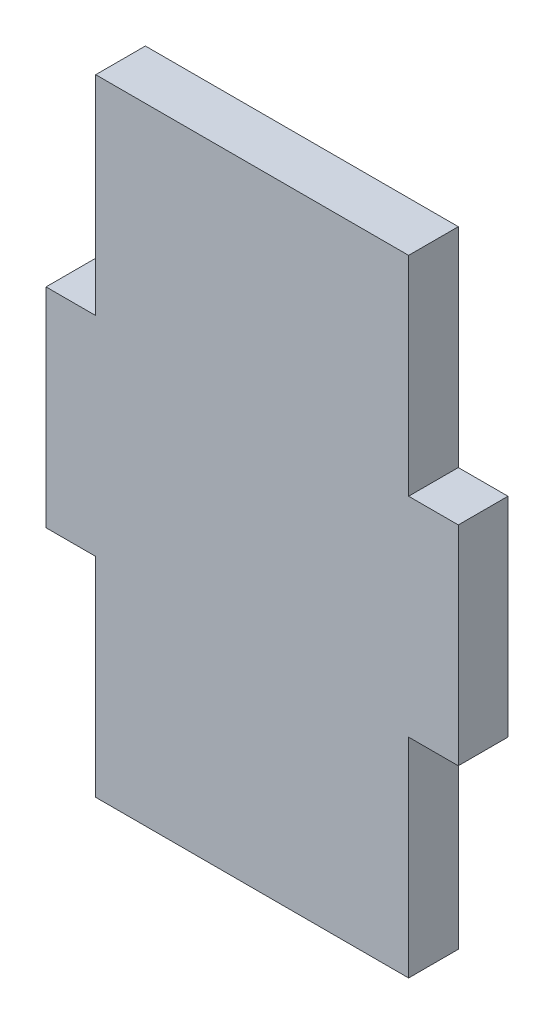
SolidWorks part; units mm, degrees
ref_plane "Front Plane" through (0, 0, 0) normal (0, 0, 1) x (1, 0, 0)
ref_plane "Top Plane" through (0, 0, 0) normal (0, 1, 0) x (1, 0, 0)
ref_plane "Right Plane" through (0, 0, 0) normal (1, 0, 0) x (0, 0, -1)
sketch "Sketch1" plane through (0, 0, 0) normal (0, 0, 1) x (1, 0, 0)
  line L0 (0, 26.6667) -> (-3.175, 26.6667)
  line L1 (0, 0) -> (20, 0)
  line L2 (0, 0) -> (0, 13.3333)
  line L3 (0, 40) -> (20, 40)
  line L4 (20, 0) -> (20, 13.3333)
  line L5 (-3.175, 26.6667) -> (-3.175, 13.3333)
  line L6 (-3.175, 13.3333) -> (0, 13.3333)
  line L7 (20, 26.6667) -> (23.175, 26.6667)
  line L8 (23.175, 26.6667) -> (23.175, 13.3333)
  line L9 (23.175, 13.3333) -> (20, 13.3333)
  line L10 (0, 26.6667) -> (0, 40)
  line L11 (20, 26.6667) -> (20, 40)
  dimension "D1" = 40
  dimension "D2" = 20
  dimension "D3" = 3.175
  dimension "D4" = 3.175
extrude "Boss-Extrude1" add sketch "Sketch1" along normal blind 3.175
